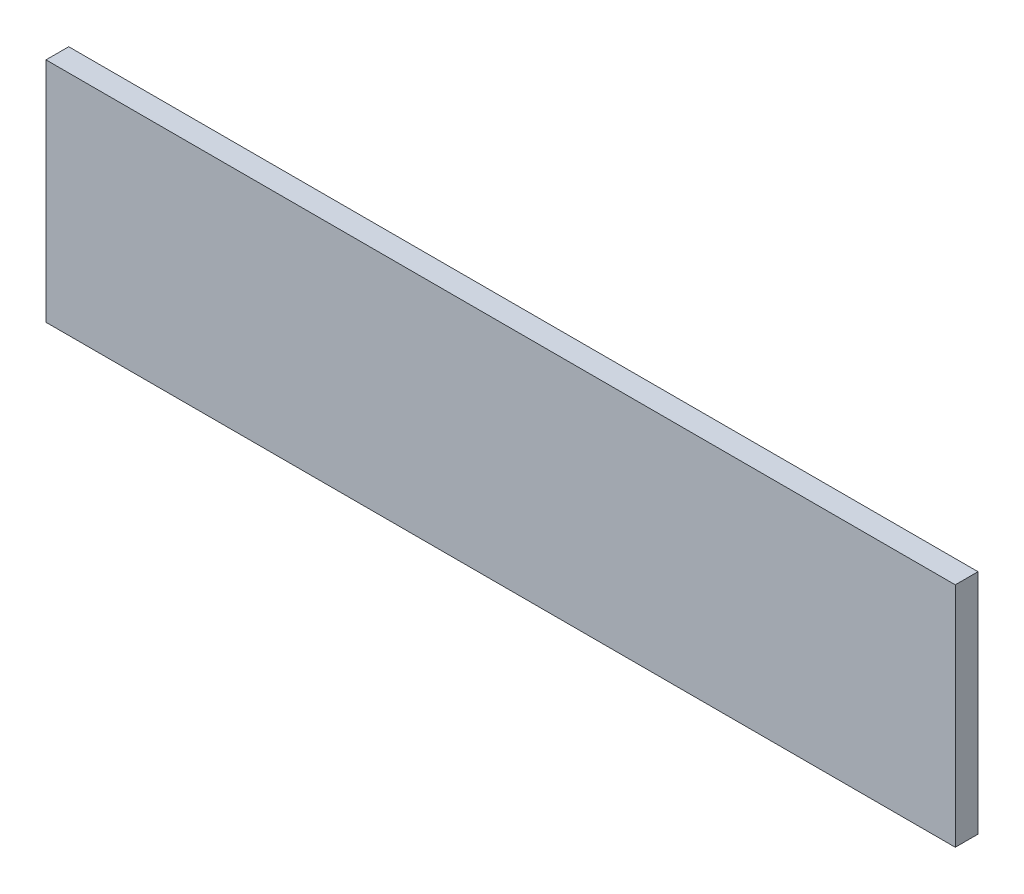
SolidWorks part; units mm, degrees
ref_plane "Plan de face" through (0, 0, 0) normal (0, 0, 1) x (1, 0, 0)
ref_plane "Plan de dessus" through (0, 0, 0) normal (0, 1, 0) x (1, 0, 0)
ref_plane "Plan de droite" through (0, 0, 0) normal (1, 0, 0) x (0, 0, -1)
sketch "Esquisse1" plane through (0, 0, 0) normal (0, 0, 1) x (1, 0, 0)
  line L1 (-100, 25) -> (100, 25)
  line L2 (-100, 25) -> (-100, -25)
  line L3 (-100, -25) -> (100, -25)
  line L4 (100, 25) -> (100, -25)
  line L5 (-100, 25) -> (100, -25) construction
  line L6 (-100, -25) -> (100, 25) construction
  point P0 (0, 0)
  dimension "D1" = 200
  dimension "D2" = 50
extrude "Boss.-Extru.1" add sketch "Esquisse1" along normal blind 5
